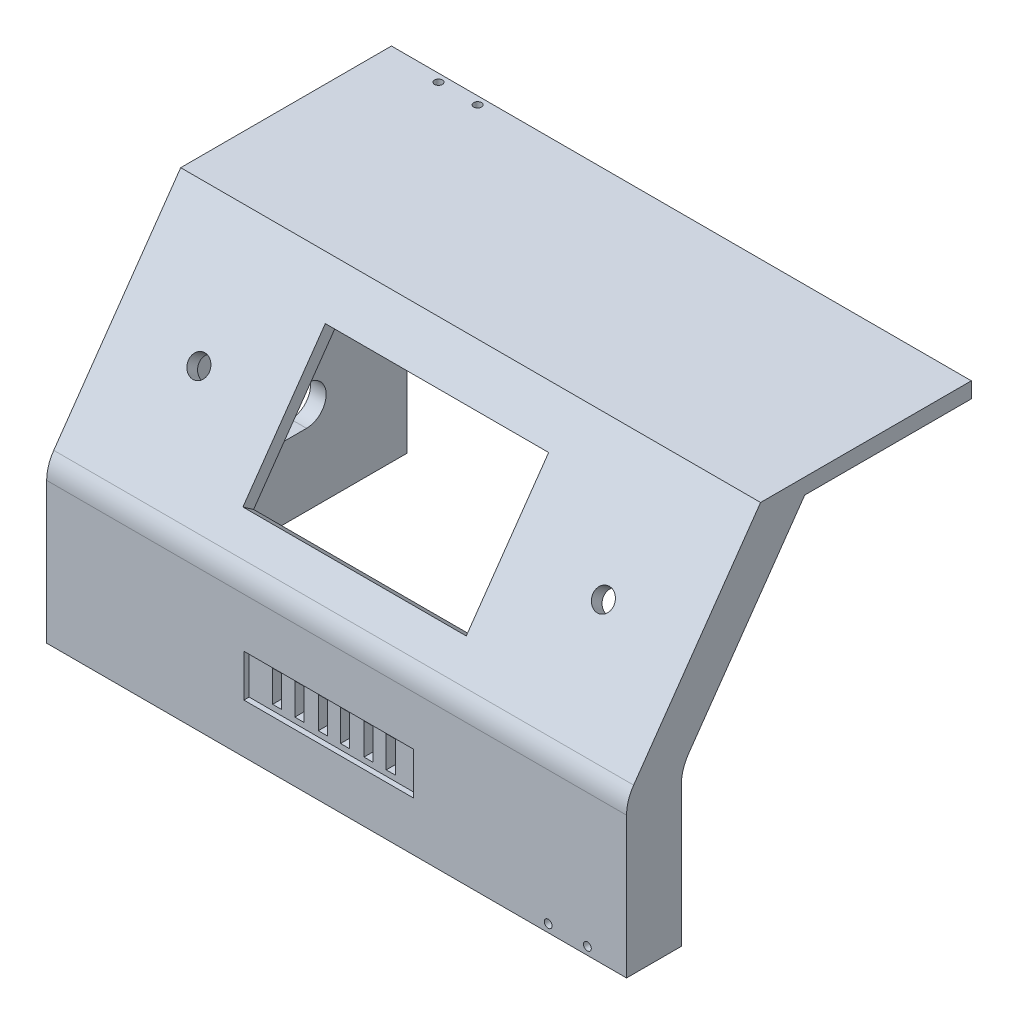
SolidWorks part; units mm, degrees
ref_plane "Front Plane" through (0, 0, 0) normal (0, 0, 1) x (1, 0, 0)
ref_plane "Top Plane" through (0, 0, 0) normal (0, 1, 0) x (1, 0, 0)
ref_plane "Right Plane" through (0, 0, 0) normal (1, 0, 0) x (0, 0, -1)
sketch "Sketch1" plane through (0, 0, 0) normal (1, 0, 0) x (0, 0, -1)
  line L0 (0, 0) -> (111, 0)
  line L1 (111, 0) -> (111, 126)
  line L2 (111, 126) -> (0, 126)
  line L3 (0, 126) -> (0, 0)
  dimension "D1" = 126
  dimension "D2" = 111
extrude "Boss-Extrude1" add sketch "Sketch1" along normal blind 6
sketch "Sketch2" plane through (0, 126, 0) normal (0, 1, 0) x (1, 0, 0)
  line L0 (0, 111) -> (0, 0)
  line L1 (0, 0) -> (216, 0)
  line L2 (216, 0) -> (216, 111)
  line L3 (216, 111) -> (0, 111)
extrude "Boss-Extrude2" add sketch "Sketch2" along normal blind 6
sketch "Sketch3" plane through (0, 0, 0) normal (0, 0, 1) x (1, 0, 0)
  line L0 (0, 132) -> (216, 132)
  line L1 (216, 132) -> (216, 0)
  line L2 (0, 132) -> (0, 0)
  line L3 (0, 0) -> (216, 0)
extrude "Boss-Extrude3" add sketch "Sketch3" along normal blind 6
sketch "Sketch4" plane through (0, 0, 6) normal (0, 0, 1) x (1, 0, 0)
  line L0 (0, 50) -> (216, 50)
  line L1 (0, 132) -> (0, 0) construction
  line L2 (216, 0) -> (216, 132) construction
  line L3 (0, 0) -> (216, 0) construction
  dimension "D1" = 50
ref_plane "Plane1" through (0, 19.2686, 27.5184) normal (0, -0.5736, -0.8192) x (1, 0, 0)
sketch "Sketch5" plane through (0, 19.2686, 27.5184) normal (0, -0.5736, -0.8192) x (1, 0, 0)
  line L0 (0, -37.5161) -> (0, -137.5025)
  line L1 (0, -137.5025) -> (216, -137.5025)
  line L2 (216, -137.5025) -> (216, -37.5161)
  line L3 (216, -37.5161) -> (0, -37.5161)
  line L4 (216, -103.2132) -> (216, -166.8801) construction
extrude "Cut-Extrude1" cut sketch "Sketch5" against normal blind 75
sketch "Sketch7" plane through (0, 19.2686, 27.5184) normal (0, -0.5736, -0.8192) x (1, 0, 0)
  line L0 (0, -137.5025) -> (0, -37.5161)
  line L1 (0, -37.5161) -> (216, -37.5161)
  line L2 (216, -37.5161) -> (216, -137.5025)
  line L3 (216, -137.5025) -> (0, -137.5025)
extrude "Boss-Extrude4" add sketch "Sketch7" against normal blind 5
sketch "Sketch8" plane through (216, 0, 0) normal (1, 0, 0) x (0, 0, -1)
  line L0 (-6, 50) -> (-6, 58.7172)
  line L1 (47.2541, 134.7719) -> (-10.0958, 52.8679) construction
  line L2 (-6, 58.7172) -> (-10.0958, 52.8679)
  line L3 (-10.0958, 52.8679) -> (-6, 50)
  line L4 (51.2127, 132) -> (45.3131, 132)
  line L5 (45.3131, 132) -> (47.2541, 134.7719)
  line L6 (47.2541, 134.7719) -> (51.2127, 132)
extrude "Cut-Extrude2" cut sketch "Sketch8" against normal blind 314
sketch "Sketch9" plane through (0, 22.1365, 31.6141) normal (0, 0.5736, 0.8192) x (1, 0, 0)
  line L0 (108, 134.1186) -> (108, 44.6569) construction
  line L1 (0, 134.1186) -> (216, 134.1186) construction
  line L2 (216, 44.6569) -> (0, 44.6569) construction
  line L3 (0, 89.3878) -> (216, 89.3878) construction
  line L4 (0, 44.6569) -> (0, 134.1186) construction
  line L5 (216, 134.1186) -> (216, 44.6569) construction
  line L6 (65.25, 116.8878) -> (150.75, 116.8878)
  line L7 (65.25, 116.8878) -> (65.25, 61.8878)
  line L8 (65.25, 61.8878) -> (150.75, 61.8878)
  line L9 (150.75, 61.8878) -> (150.75, 116.8878)
  dimension "D1" = 85.5
  dimension "D2" = 55
extrude "Cut-Extrude3" cut sketch "Sketch9" against normal blind 14
fillet "Fillet1" radius 15 2 edges at (111, 58.5689, 0) (108, 58.7172, 6)
sketch "Sketch10" plane through (0, 0, 0) normal (-1, 0, 0) x (0, 0, 1)
  line L0 (6, 35) -> (-111, 35) construction
  line L1 (6, 53.9878) -> (6, 0) construction
  line L2 (-111, 0) -> (-111, 132) construction
  line L3 (-87.5, 35) -> (-17.5, 35) construction
  line L4 (-87.5, 42.5) -> (-17.5, 42.5)
  line L5 (-87.5, 27.5) -> (-17.5, 27.5)
  line L6 (6, 0) -> (-111, 0) construction
  line L7 (-111, 92) -> (-17.3048, 92) construction
  line L8 (3.2873, 62.5914) -> (-45.3131, 132) construction
  line L9 (-89.1524, 92) -> (-39.1524, 92) construction
  line L10 (-89.1524, 99.5) -> (-39.1524, 99.5)
  line L11 (-89.1524, 84.5) -> (-39.1524, 84.5)
  arc A0 (-87.5, 42.5) -> (-87.5, 27.5) centre (-87.5, 35) ccw
  arc A1 (-17.5, 27.5) -> (-17.5, 42.5) centre (-17.5, 35) ccw
  arc A2 (-89.1524, 99.5) -> (-89.1524, 84.5) centre (-89.1524, 92) ccw
  arc A3 (-39.1524, 84.5) -> (-39.1524, 99.5) centre (-39.1524, 92) ccw
  point P8 (-52.5, 35)
  point P21 (-64.1524, 92)
  dimension "D1" = 15
  dimension "D2" = 35
  dimension "D3" = 15
  dimension "D4" = 40
  dimension "D5" = 70
  dimension "D6" = 50
extrude "Cut-Extrude4" cut sketch "Sketch10" against normal blind 27
sketch "Sketch11" plane through (0, 0, 6) normal (0, 0, 1) x (1, 0, 0)
  line L0 (108, 53.9878) -> (108, 0) construction
  line L1 (216, 53.9878) -> (0, 53.9878) construction
  line L2 (0, 0) -> (216, 0) construction
  line L3 (0, 26.9939) -> (216, 26.9939) construction
  line L4 (0, 53.9878) -> (0, 0) construction
  line L5 (216, 0) -> (216, 53.9878) construction
  line L6 (75.5, 35.0939) -> (140.5, 35.0939)
  line L7 (75.5, 35.0939) -> (75.5, 18.8939)
  line L8 (75.5, 18.8939) -> (140.5, 18.8939)
  line L9 (140.5, 18.8939) -> (140.5, 35.0939)
  dimension "D1" = 65
  dimension "D2" = 16.2
extrude "Cut-Extrude5" cut sketch "Sketch11" against normal blind 2
sketch "Sketch12" plane through (0, 0, 4) normal (0, 0, 1) x (1, 0, 0)
  line L0 (108, 35.0939) -> (108, 18.8939) construction
  line L1 (140.5, 35.0939) -> (75.5, 35.0939) construction
  line L2 (75.5, 18.8939) -> (140.5, 18.8939) construction
  line L3 (75.5, 26.9939) -> (140.5, 26.9939) construction
  line L4 (75.5, 35.0939) -> (75.5, 18.8939) construction
  line L5 (140.5, 18.8939) -> (140.5, 35.0939) construction
  line L6 (90.5, 35.0939) -> (90.5, 18.8939) construction
  line L7 (75.5, 18.8939) -> (140.5, 18.8939) construction
  line L8 (125.5, 35.0939) -> (125.5, 18.8939) construction
  line L9 (140.5, 35.0939) -> (75.5, 35.0939) construction
  line L10 (140.5, 18.8939) -> (140.5, 35.0939) construction
  line L11 (84.5, 32.9939) -> (88, 32.9939)
  line L12 (88, 32.9939) -> (88, 20.9939)
  line L13 (88, 20.9939) -> (84.5, 20.9939)
  line L14 (84.5, 20.9939) -> (84.5, 32.9939)
  line L15 (96.5, 32.9939) -> (96.5, 20.9939)
  line L16 (93, 20.9939) -> (93, 32.9939)
  line L17 (93, 32.9939) -> (96.5, 32.9939)
  line L18 (96.5, 20.9939) -> (93, 20.9939)
  line L19 (99.25, 35.0939) -> (99.25, 18.8939) construction
  line L20 (105.5, 32.9939) -> (102, 32.9939)
  line L21 (105.5, 20.9939) -> (105.5, 32.9939)
  line L22 (102, 20.9939) -> (105.5, 20.9939)
  line L23 (102, 32.9939) -> (102, 20.9939)
  line L24 (110.5, 20.9939) -> (114, 20.9939)
  line L25 (110.5, 32.9939) -> (110.5, 20.9939)
  line L26 (114, 32.9939) -> (110.5, 32.9939)
  line L27 (114, 20.9939) -> (114, 32.9939)
  line L28 (116.75, 35.0939) -> (116.75, 18.8939) construction
  line L29 (123, 32.9939) -> (123, 20.9939)
  line L30 (119.5, 32.9939) -> (123, 32.9939)
  line L31 (119.5, 20.9939) -> (119.5, 32.9939)
  line L32 (123, 20.9939) -> (119.5, 20.9939)
  line L33 (128, 20.9939) -> (128, 32.9939)
  line L34 (131.5, 20.9939) -> (128, 20.9939)
  line L35 (131.5, 32.9939) -> (131.5, 20.9939)
  line L36 (128, 32.9939) -> (131.5, 32.9939)
  dimension "D1" = 15
  dimension "D2" = 15
  dimension "D3" = 12
  dimension "D4" = 3.5
  dimension "D5" = 3.5
  dimension "D6" = 12
  dimension "D7" = 12
  dimension "D8" = 12
  dimension "D9" = 2.5
  dimension "D10" = 2.5
  dimension "D11" = 8.75
  dimension "D12" = 8.75
extrude "Cut-Extrude6" cut sketch "Sketch12" against normal blind 11
sketch "Sketch13" plane through (216, 0, 0) normal (1, 0, 0) x (0, 0, -1)
  line L0 (111, 126) -> (111, 132)
  line L1 (111, 132) -> (45.3131, 132)
  line L2 (45.3131, 132) -> (-3.2873, 62.5914)
  line L3 (-6, 53.9878) -> (-6, 0)
  line L4 (-6, 0) -> (0, 0)
  line L5 (0, 0) -> (0, 53.8394)
  line L6 (2.7127, 62.4431) -> (47.2158, 126)
  line L7 (47.2158, 126) -> (111, 126)
  arc A0 (-3.2873, 62.5914) -> (-6, 53.9878) centre (9, 53.9878) ccw
  arc A1 (0, 53.8394) -> (2.7127, 62.4431) centre (15, 53.8394) cw
extrude "Boss-Extrude5" add sketch "Sketch13" along normal blind 6
sketch "Sketch22" plane through (0, 0, 6) normal (0, 0, 1) x (1, 0, 0)
  line L0 (222, 6) -> (222, 0) construction
  line L1 (222, 53.9878) -> (222, 0) construction
  line L2 (222, 3) -> (97.2764, 3) construction
  line L3 (207, 7.7889) -> (207, 0) construction
  line L4 (0, 0) -> (222, 0) construction
  line L5 (192, 6) -> (192, 0) construction
  circle A0 centre (207, 3) radius 1.5
  circle A1 centre (192, 3) radius 1.5
  dimension "D1" = 6
  dimension "D2" = 15
  dimension "D3" = 15
extrude "Cut-Extrude13" cut sketch "Sketch22" against normal blind 20
sketch "Sketch24" plane through (0, 0, -111) normal (0, 0, -1) x (-1, 0, 0)
  line L0 (-222, 132) -> (-222, 126)
  line L1 (-222, 126) -> (-6, 126)
  line L2 (-6, 126) -> (-6, 0)
  line L3 (-6, 0) -> (0, 0)
  line L4 (0, 0) -> (0, 132)
  line L5 (0, 132) -> (-222, 132)
extrude "Boss-Extrude6" add sketch "Sketch24" along normal blind 15
sketch "Sketch25" plane through (0, 132, 0) normal (0, 1, 0) x (1, 0, 0)
  line L0 (0, 126) -> (0, 120) construction
  line L1 (0, 126) -> (0, 45.3131) construction
  line L2 (0, 123) -> (132.2621, 123) construction
  line L3 (6, 126) -> (6, 47.2158) construction
  circle A0 centre (21, 123) radius 1.5
  circle A1 centre (36, 123) radius 1.5
  dimension "D1" = 15
  dimension "D2" = 15
extrude "Cut-Extrude14" cut sketch "Sketch25" against normal blind 15
sketch "Sketch34" plane through (222, 0, 0) normal (1, 0, 0) x (0, 0, -1)
  line L0 (2.7127, 62.4431) -> (47.2158, 126)
  line L1 (17.7127, 62.4431) -> (62.2158, 126)
  line L2 (47.2158, 126) -> (126, 126) construction
  line L3 (47.2158, 126) -> (62.2158, 126)
  line L4 (0, 53.8394) -> (0, 0)
  line L5 (0, 0) -> (15, 0)
  line L6 (0, 0) -> (126, 0) construction
  line L7 (15, 0) -> (15, 53.8394)
  arc A0 (0, 53.8394) -> (2.7127, 62.4431) centre (15, 53.8394) cw
  arc A1 (15, 53.8394) -> (17.7127, 62.4431) centre (30, 53.8394) cw
  dimension "D1" = 15
  dimension "D2" = 15
extrude "Boss-Extrude9" add sketch "Sketch34" against normal blind 6
sketch "Sketch35" plane through (0, 0, 0) normal (0, 0, -1) x (-1, 0, 0)
  line L0 (-216, 0) -> (-6, 0)
  line L1 (-6, 0) -> (-6, 6)
  line L2 (-6, 53.8394) -> (-6, 0) construction
  line L3 (-6, 6) -> (-216, 6)
  line L4 (-216, 0) -> (-216, 53.8394) construction
  line L5 (-216, 6) -> (-216, 0)
  circle A0 centre (-207, 3) radius 1.5
  circle A1 centre (-192, 3) radius 1.5
extrude "Boss-Extrude10" add sketch "Sketch35" along normal blind 15
sketch "Sketch36" plane through (0, 22.1365, 31.6141) normal (0, 0.5736, 0.8192) x (1, 0, 0)
  line L0 (150.75, 89.3878) -> (222, 89.3878) construction
  line L1 (150.75, 61.8878) -> (150.75, 116.8878) construction
  line L2 (222, 134.1186) -> (222, 49.3864) construction
  line L3 (187.4776, 134.1186) -> (187.4776, 49.3864) construction
  line L4 (0, 134.1186) -> (222, 134.1186) construction
  line L5 (0, 49.3864) -> (222, 49.3864) construction
  circle A0 centre (187.4776, 89.3878) radius 4
extrude "Cut-Extrude16" cut sketch "Sketch36" against normal blind 15
sketch "Sketch37" plane through (0, 22.1365, 31.6141) normal (0, 0.5736, 0.8192) x (1, 0, 0)
  line L0 (65.25, 89.3878) -> (0, 89.3878) construction
  line L1 (65.25, 116.8878) -> (65.25, 61.8878) construction
  line L2 (0, 49.3864) -> (0, 134.1186) construction
  circle A0 centre (32.625, 89.3878) radius 4
extrude "Cut-Extrude17" cut sketch "Sketch37" against normal blind 15
